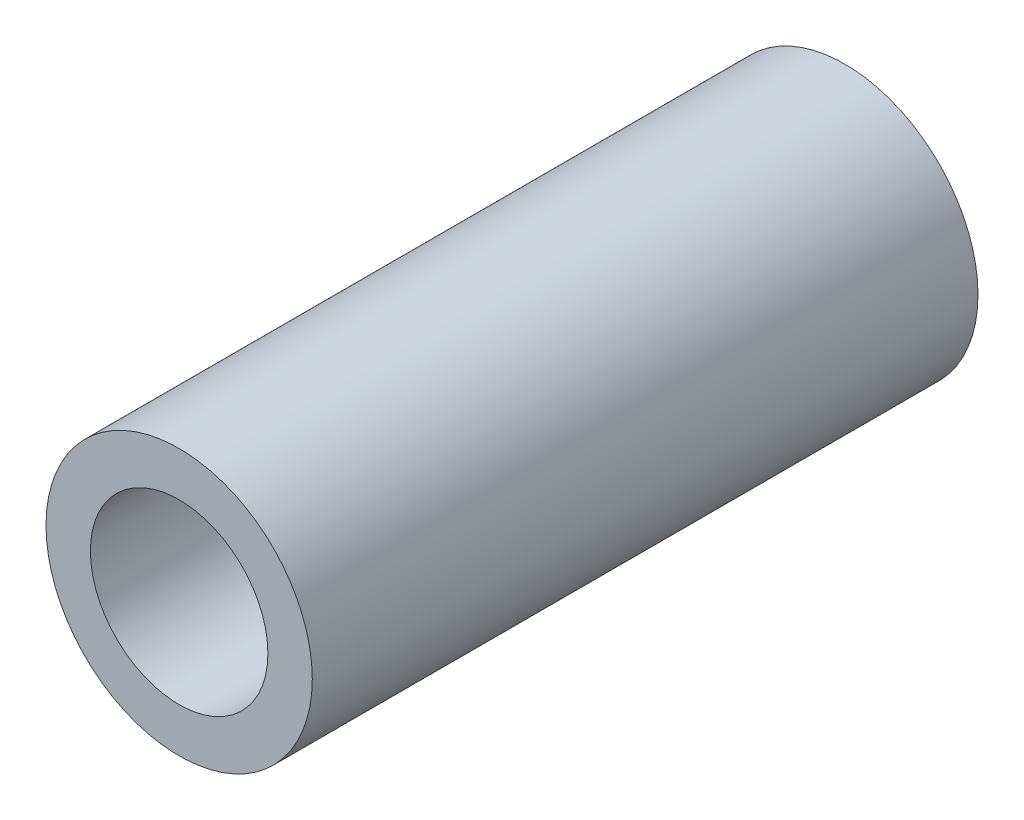
SolidWorks part; units mm, degrees
ref_plane "Front Plane" through (0, 0, 0) normal (0, 0, 1) x (1, 0, 0)
ref_plane "Top Plane" through (0, 0, 0) normal (0, 1, 0) x (1, 0, 0)
ref_plane "Right Plane" through (0, 0, 0) normal (1, 0, 0) x (0, 0, -1)
sketch "Sketch1" plane through (0, 0, 0) normal (0, 0, 1) x (1, 0, 0)
  circle A0 centre (-20, -10) radius 3
  circle A1 centre (-20, -10) radius 2
extrude "Boss-Extrude1" add sketch "Sketch1" along normal blind 15
